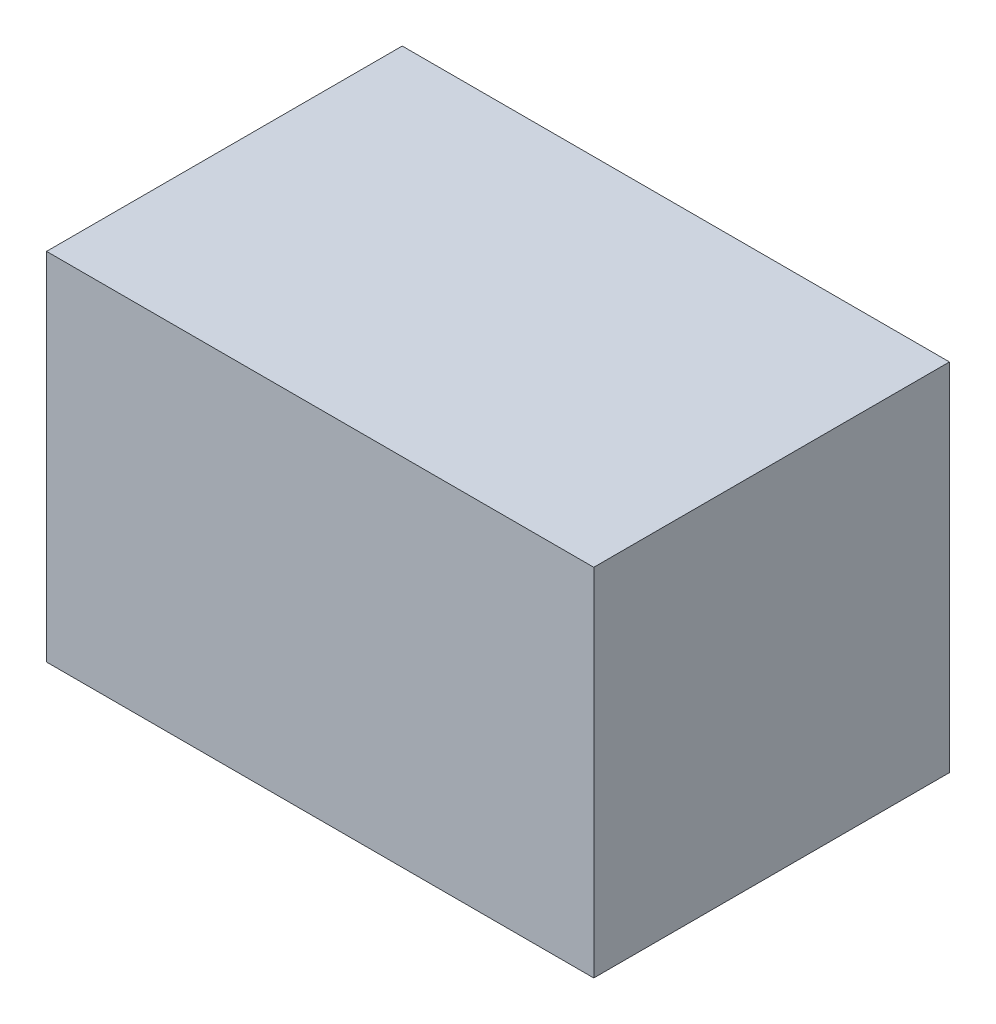
SolidWorks part; units mm, degrees
ref_plane "Front Plane" through (0, 0, 0) normal (0, 0, 1) x (1, 0, 0)
ref_plane "Top Plane" through (0, 0, 0) normal (0, 1, 0) x (1, 0, 0)
ref_plane "Right Plane" through (0, 0, 0) normal (1, 0, 0) x (0, 0, -1)
sketch "Sketch1" plane through (0, 0, 0) normal (0, 1, 0) x (1, 0, 0)
  line L1 (100, -65) -> (-100, -65)
  line L2 (100, -65) -> (100, 65)
  line L3 (100, 65) -> (-100, 65)
  line L4 (-100, -65) -> (-100, 65)
  line L5 (100, -65) -> (-100, 65) construction
  line L6 (100, 65) -> (-100, -65) construction
  point P0 (0, 0)
  dimension "D1" = 200
  dimension "D2" = 130
extrude "Boss-Extrude1" add sketch "Sketch1" along normal blind 130
